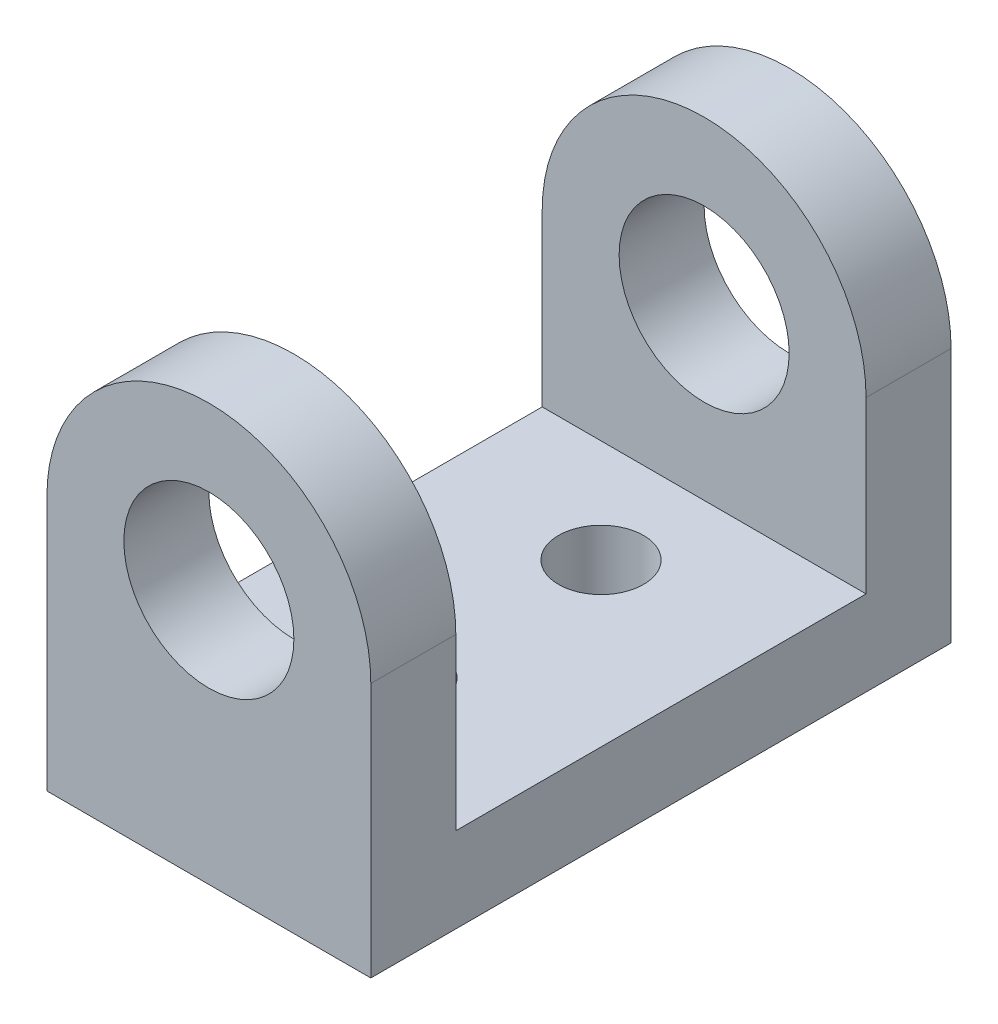
SolidWorks part; units mm, degrees
ref_plane "Front Plane" through (0, 0, 0) normal (0, 0, 1) x (1, 0, 0)
ref_plane "Top Plane" through (0, 0, 0) normal (0, 1, 0) x (1, 0, 0)
ref_plane "Right Plane" through (0, 0, 0) normal (1, 0, 0) x (0, 0, -1)
sketch "Sketch1" plane through (0, 0, 0) normal (0, 0, 1) x (1, 0, 0)
  line L0 (-9.525, 0) -> (-9.525, -15)
  line L1 (-9.525, -15) -> (9.525, -15)
  line L2 (9.525, -15) -> (9.525, 0)
  circle A0 centre (0, 0) radius 9.525
  circle A1 centre (0, 0) radius 5
  dimension "D1" = 19.05
  dimension "D2" = 10
  dimension "D3" = 15
extrude "Boss-Extrude1" add sketch "Sketch1" along normal blind 34.13 contours A0 A1 | A0 L0 L1 L2
sketch "Sketch2" plane through (9.525, 0, 0) normal (1, 0, 0) x (0, 0, -1)
  line L0 (-17.065, 9.525) -> (-17.065, -15) construction
  line L1 (0, 9.525) -> (-34.13, 9.525) construction
  line L2 (-34.13, -15) -> (0, -15) construction
  line L3 (0, -15) -> (0, 0) construction
  line L4 (-29.13, 9.525) -> (-5, 9.525)
  line L5 (-29.13, 9.525) -> (-29.13, -10)
  line L6 (-29.13, -10) -> (-5, -10)
  line L7 (-5, 9.525) -> (-5, -10)
  line L8 (-34.13, 9.525) -> (-34.13, 0) construction
  dimension "D1" = 5
  dimension "D2" = 5
  dimension "D3" = 5
extrude "Cut-Extrude1" cut sketch "Sketch2" against normal through all
sketch "Sketch3" plane through (0, -10, 0) normal (0, 1, 0) x (1, 0, 0)
  line L0 (9.525, -17.065) -> (-9.525, -17.065) construction
  line L1 (9.525, -29.13) -> (9.525, -5) construction
  line L2 (-9.525, -29.13) -> (-9.525, -5) construction
  circle A0 centre (0, -11.065) radius 2.5
  circle A1 centre (0, -23.065) radius 2.5
  point P8 (0, -17.065)
  dimension "D1" = 5
  dimension "D2" = 6
extrude "Cut-Extrude2" cut sketch "Sketch3" against normal through all
